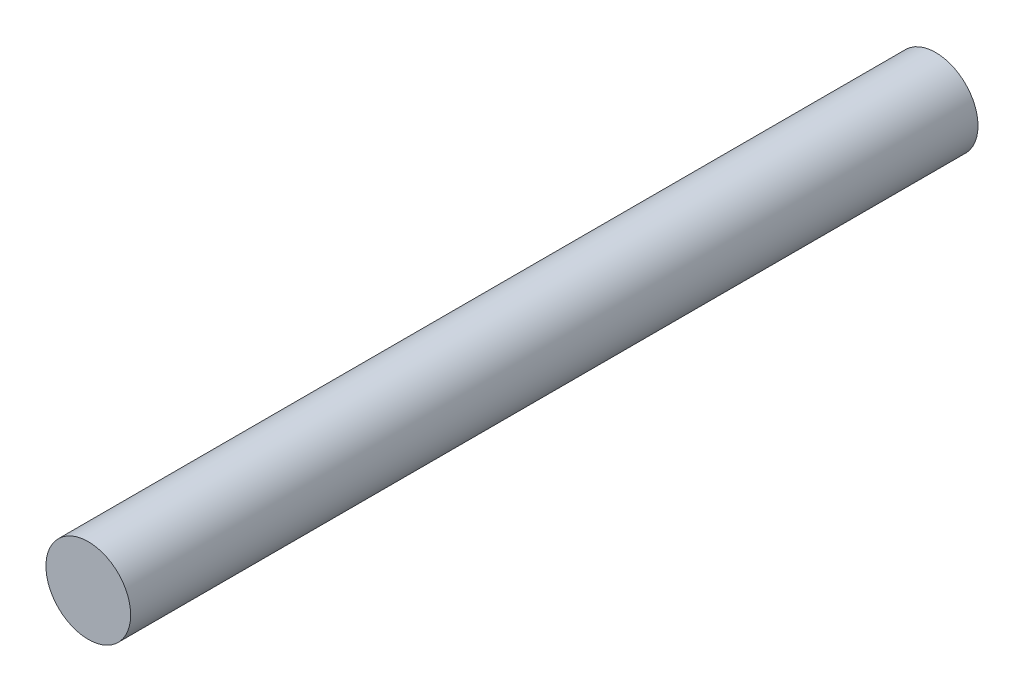
SolidWorks part; units mm, degrees
ref_plane "前视基准面" through (0, 0, 0) normal (0, 0, 1) x (1, 0, 0)
ref_plane "上视基准面" through (0, 0, 0) normal (0, 1, 0) x (1, 0, 0)
ref_plane "右视基准面" through (0, 0, 0) normal (1, 0, 0) x (0, 0, -1)
other "Configuration Table"
sketch "草图1" plane through (0, 0, 0) normal (0, 0, 1) x (1, 0, 0)
  circle A0 centre (0, 0) radius 1.25
  dimension "D1" = 2.5
extrude "凸台-拉伸1" add sketch "草图1" along normal blind 25
